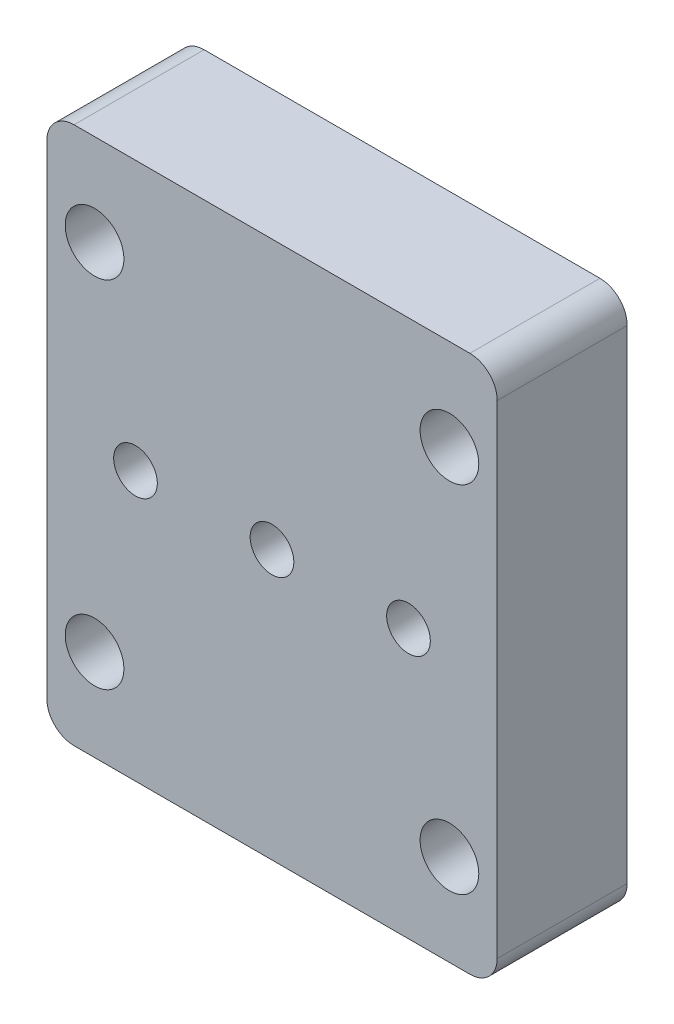
SolidWorks part; units mm, degrees
material "AISI 1045 Steel, cold drawn"
ref_plane "Front Plane" through (0, 0, 0) normal (0, 0, 1) x (1, 0, 0)
ref_plane "Top Plane" through (0, 0, 0) normal (0, 1, 0) x (1, 0, 0)
ref_plane "Right Plane" through (0, 0, 0) normal (1, 0, 0) x (0, 0, -1)
sketch "Sketch1" plane through (0, 0, 0) normal (0, 0, 1) x (1, 0, 0)
  line L0 (10, 0) -> (-10, 0) construction
  line L1 (13, -13) -> (-13, -13) construction
  line L2 (13, -13) -> (13, 13) construction
  line L3 (13, 13) -> (-13, 13) construction
  line L4 (-13, -13) -> (-13, 13) construction
  line L5 (13, -13) -> (-13, 13) construction
  line L6 (13, 13) -> (-13, -13) construction
  line L7 (16.5, -19.7) -> (-16.5, -19.7)
  line L8 (16.5, -19.7) -> (16.5, 19.7)
  line L9 (16.5, 19.7) -> (-16.5, 19.7)
  line L10 (-16.5, -19.7) -> (-16.5, 19.7)
  line L11 (16.5, -19.7) -> (-16.5, 19.7) construction
  line L12 (16.5, 19.7) -> (-16.5, -19.7) construction
  point P0 (0, 0)
  point P6 (0, 0)
  point P14 (0, 0)
  dimension "D1" = 26
  dimension "D2" = 20
  dimension "D3" = 33
  dimension "D4" = 39.4
extrude "Boss-Extrude1" add sketch "Sketch1" along normal blind 9.525
hole_wizard "M3 Clearance Hole1" positions "Sketch2" profile "Sketch3" hole size "M3" standard "ANSI Metric" end condition through all
sketch "Sketch2" plane through (0, 0, 9.525) normal (0, 0, 1) x (1, 0, 0)
  line L0 (13, 13) -> (-13, -13) construction
  point P0 (-10, 0)
  point P3 (0, 0)
  point P7 (10, 0)
sketch "Sketch3" plane through (-10, 0, 9.525) normal (1, 0, 0) x (0, -1, 0)
  line L0 (0, 0) -> (0, 9.525)
  line L1 (0, 9.525) -> (1.6, 9.525)
  line L2 (1.6, 9.525) -> (1.6, 0)
  line L5 (1.6, 0) -> (0, 0)
  line L11 (0, -6.35) -> (0, 107.95) construction
  dimension "Thru Hole Dia." = 3.2
  dimension "Thru Hole Depth" = 9.525
hole_wizard "M4 Clearance Hole1" positions "Sketch4" profile "Sketch5" hole size "M4" standard "ANSI Metric" end condition through all
sketch "Sketch4" plane through (0, 0, 9.525) normal (0, 0, 1) x (1, 0, 0)
  point P0 (-13, 13)
  point P3 (-13, -13)
  point P6 (13, -13)
  point P9 (13, 13)
sketch "Sketch5" plane through (-13, 13, 9.525) normal (1, 0, 0) x (0, -1, 0)
  line L0 (0, 0) -> (0, 9.525)
  line L1 (0, 9.525) -> (2.15, 9.525)
  line L2 (2.15, 9.525) -> (2.15, 0)
  line L5 (2.15, 0) -> (0, 0)
  line L11 (0, -6.35) -> (0, 107.95) construction
  dimension "Thru Hole Dia." = 4.3
  dimension "Thru Hole Depth" = 9.525
fillet "Fillet1" radius 2 4 edges at (16.5, 19.7, 4.7625) (16.5, -19.7, 4.7625) (-16.5, -19.7, 4.7625) (-16.5, 19.7, 4.7625)
